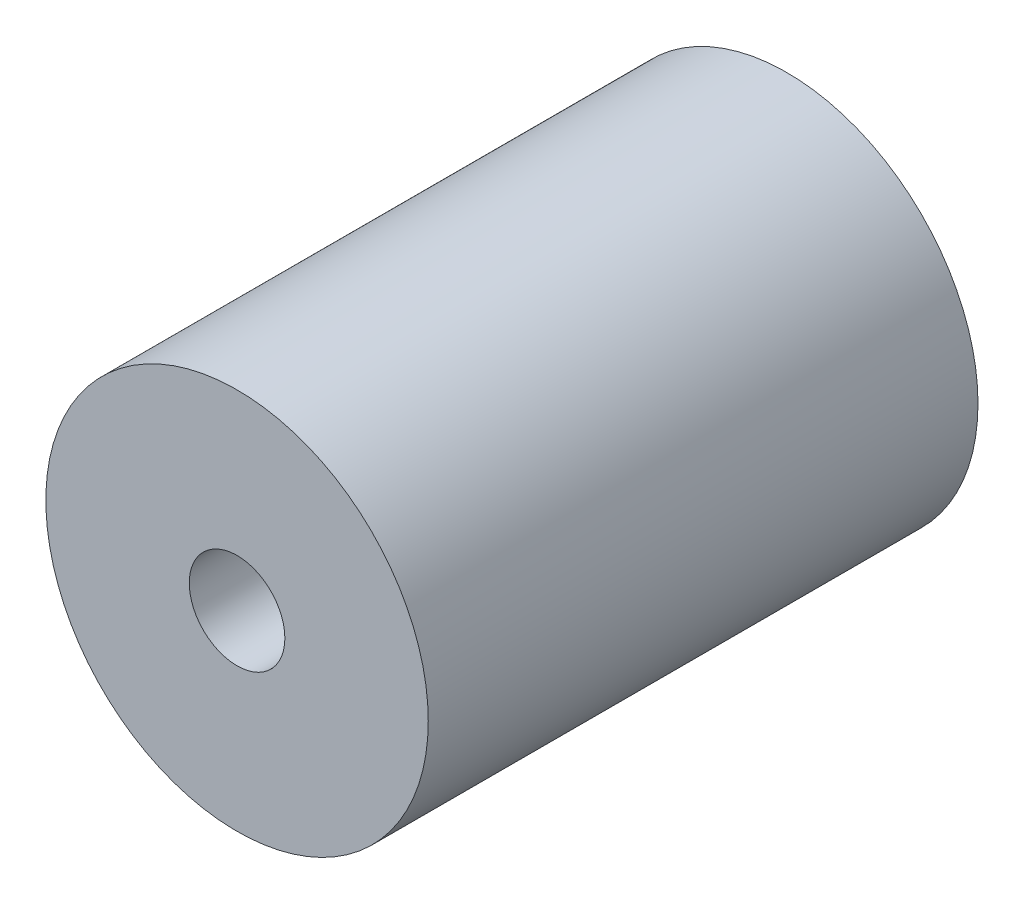
SolidWorks part; units mm, degrees
ref_plane "Front Plane" through (0, 0, 0) normal (0, 0, 1) x (1, 0, 0)
ref_plane "Top Plane" through (0, 0, 0) normal (0, 1, 0) x (1, 0, 0)
ref_plane "Right Plane" through (0, 0, 0) normal (1, 0, 0) x (0, 0, -1)
sketch "Sketch1" plane through (0, 0, 0) normal (0, 0, 1) x (1, 0, 0)
  circle A0 centre (0, 0) radius 8
  circle A1 centre (0, 0) radius 2
  dimension "D1" = 16
  dimension "D2" = 4
extrude "Boss-Extrude1" add sketch "Sketch1" along normal blind 23
